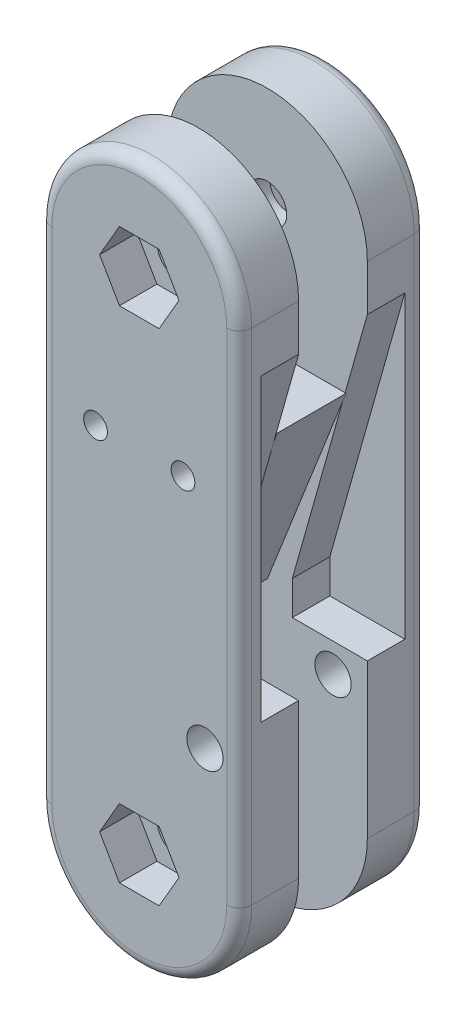
SolidWorks part; units mm, degrees
ref_plane "Front Plane" through (0, 0, 0) normal (0, 0, 1) x (1, 0, 0)
ref_plane "Top Plane" through (0, 0, 0) normal (0, 1, 0) x (1, 0, 0)
ref_plane "Right Plane" through (0, 0, 0) normal (1, 0, 0) x (0, 0, -1)
sketch "Sketch1" plane through (0, 0, 0) normal (0, 0, 1) x (1, 0, 0)
  line L0 (0, 0) -> (0, 40) construction
  line L1 (-8, 0) -> (-8, 40)
  line L2 (8, 0) -> (8, 40)
  arc A0 (-8, 0) -> (8, 0) centre (0, 0) ccw
  arc A1 (8, 40) -> (-8, 40) centre (0, 40) ccw
  circle A2 centre (0, 40) radius 1.55
  circle A3 centre (0, 0) radius 1.55
  circle A4 centre (5.258, 10) radius 1.45
  point P3 (0, 20)
  dimension "D1" = 3.1
  dimension "D2" = 8
  dimension "D3" = 40
  dimension "D4" = 2.9
  dimension "D5" = 10
extrude "Boss-Extrude1" add sketch "Sketch1" along normal blind 4.75
fillet "Fillet2" radius 1 4 edges at (-8, 20, 4.75) (0, 48, 4.75) (8, 20, 4.75) (0, -8, 4.75)
sketch "Sketch2" plane through (0, 0, 4.75) normal (0, 0, 1) x (1, 0, 0)
  line L1 (3.1754, 40) -> (1.5877, 42.75)
  line L2 (1.5877, 42.75) -> (-1.5877, 42.75)
  line L3 (-1.5877, 42.75) -> (-3.1754, 40)
  line L4 (-3.1754, 40) -> (-1.5877, 37.25)
  line L5 (-1.5877, 37.25) -> (1.5877, 37.25)
  line L6 (1.5877, 37.25) -> (3.1754, 40)
  line L7 (3.1754, 0) -> (1.5877, 2.75)
  line L8 (1.5877, 2.75) -> (-1.5877, 2.75)
  line L9 (-1.5877, 2.75) -> (-3.1754, 0)
  line L10 (-3.1754, 0) -> (-1.5877, -2.75)
  line L11 (-1.5877, -2.75) -> (1.5877, -2.75)
  line L12 (1.5877, -2.75) -> (3.1754, 0)
  circle A0 centre (0, 40) radius 2.75 construction
  circle A1 centre (0, 0) radius 2.75 construction
  dimension "D1" = 5.5
extrude "Cut-Extrude1" cut sketch "Sketch2" against normal blind 3
sketch "Sketch3" plane through (0, 0, 0) normal (0, 0, -1) x (-1, 0, 0)
  line L0 (8, 40) -> (8, 0) construction
  line L1 (8, 30) -> (3, 30)
  line L2 (8, 30) -> (8, 12)
  line L3 (8, 12) -> (3, 12)
  line L4 (3, 30) -> (3, 12) construction
  line L5 (3, 30) -> (-6.305, 30)
  line L7 (-6.305, 30) -> (0, 14)
  line L8 (0, 14) -> (3, 12)
  circle A0 centre (0, 40) radius 1.55 construction
  circle A1 centre (0, 0) radius 1.55 construction
  dimension "D1" = 5
  dimension "D2" = 10
  dimension "D3" = 12
extrude "Boss-Extrude2" add sketch "Sketch3" along normal blind 2.75
mirror "Mirror5" about plane through (0, 0, -2.75) normal (0, 0, 1) of bodies 103
sketch "Sketch4" plane through (0, 0, -5.5) normal (0, 0, 1) x (1, 0, 0)
  line L0 (2, 12.3059) -> (2, 15.0235)
  line L1 (2, 15.0235) -> (8, 36.3059)
  line L2 (8, 40) -> (8, 0) construction
  line L3 (8, 36.3059) -> (8, 12.3059)
  line L5 (2, 12.3059) -> (8, 12.3059)
  dimension "D1" = 6
  dimension "D2" = 24
extrude "Cut-Extrude2" cut sketch "Sketch4" against normal blind 3
sketch "Sketch6" plane through (0, 0, -10.25) normal (0, 0, -1) x (-1, 0, 0)
  line L0 (0, 42.75) -> (0, 45.4685) construction
  line L1 (-6.725, 42) -> (-5.525, 42)
  line L2 (-6.725, 42) -> (-6.725, 36)
  line L3 (-6.725, 36) -> (-5.525, 36)
  line L4 (-5.525, 42) -> (-5.525, 36)
  line L10 (0, 40) -> (5.2045, 40) construction
  line L11 (5.525, 42) -> (5.525, 36)
  line L12 (6.725, 36) -> (5.525, 36)
  line L13 (6.725, 42) -> (6.725, 36)
  line L14 (6.725, 42) -> (5.525, 42)
  dimension "D1" = 11.05
  dimension "D2" = 1.2
  dimension "D3" = 6
  dimension "D4" = 2
extrude "Boss-Extrude3" [suppressed] add sketch "Sketch6" along normal blind 4
chamfer "Chamfer1" [suppressed] distance 1.5 angle 45
ref_plane "Plane1" through (0, 0, -2.75) normal (0, 0, -1) x (-1, 0, 0)
mirror "Mirror6" about plane through (0, 0, -2.75) normal (0, 0, -1) of "Cut-Extrude2"
sketch "Sketch7" plane through (0, 0, -10.25) normal (0, 0, -1) x (-1, 0, 0)
  line L0 (0, 40) -> (0, 18.9568) construction
  circle A0 centre (-3.5, 28) radius 0.95
  circle A1 centre (0, 40) radius 1.55 construction
  circle A2 centre (3.5, 28) radius 0.95
  dimension "D1" = 1.9
  dimension "D2" = 7
  dimension "D3" = 12
extrude "Cut-Extrude3" cut sketch "Sketch7" against normal through all
